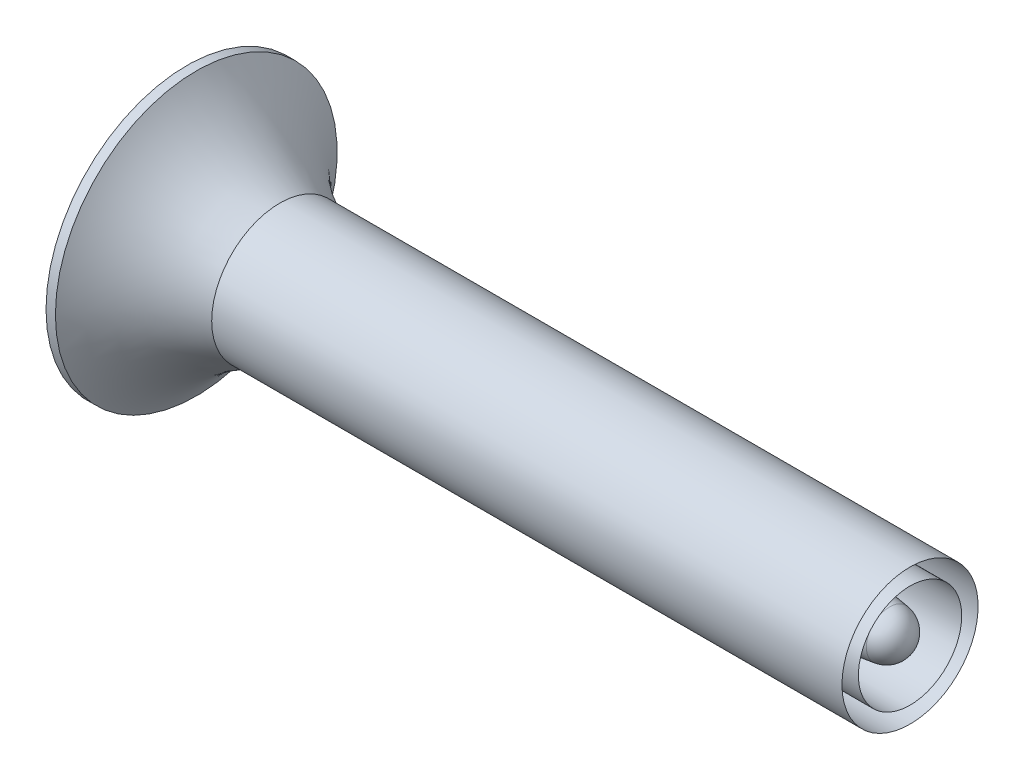
SolidWorks part; units mm, degrees
ref_plane "Front Plane" through (0, 0, 0) normal (0, 0, 1) x (1, 0, 0)
ref_plane "Top Plane" through (0, 0, 0) normal (0, 1, 0) x (1, 0, 0)
ref_plane "Right Plane" through (0, 0, 0) normal (1, 0, 0) x (0, 0, -1)
sketch "Sketch1" plane through (0, 0, 0) normal (0, 0, 1) x (1, 0, 0)
  line L0 (0, -3.81) -> (0, 0)
  line L1 (0, 3.81) -> (0.254, 3.81) construction
  line L2 (0.254, 3.81) -> (1.524, 2.54) construction
  line L3 (1.524, 2.54) -> (4.572, 1.397) construction
  line L4 (4.572, 1.397) -> (4.572, -1.397) construction
  line L5 (4.572, -1.397) -> (1.524, -2.54) construction
  line L6 (1.524, -2.54) -> (0.254, -3.81) construction
  line L7 (0.254, -3.81) -> (0, -3.81)
  line L8 (0.254, 3.81) -> (0.254, -3.81) construction
  line L9 (1.524, 2.54) -> (1.524, -2.54) construction
  line L10 (0, 0) -> (18.923, 0) construction
  line L11 (4.572, 1.397) -> (13.1767, 1.397) construction
  line L12 (4.572, -1.397) -> (13.1767, -1.397)
  line L13 (13.1767, -1.397) -> (19.0059, -0.6296)
  line L14 (19.0059, 0.6296) -> (13.1767, 1.397) construction
  line L15 (13.1767, 1.397) -> (13.1767, -1.397) construction
  line L16 (19.0059, -0.6296) -> (23.7879, 0) construction
  line L17 (23.7879, 0) -> (19.0059, 0.6296) construction
  line L18 (0, 0) -> (19.558, 0)
  line L19 (0, 0) -> (0, 3.81) construction
  arc A0 (19.558, 0) -> (19.0059, -0.6296) centre (18.923, 0) cw
  arc A1 (19.0059, 0.6296) -> (19.558, 0) centre (18.923, 0) cw construction
  arc A2 (4.572, -1.397) -> (0.254, -3.81) centre (4.572, -6.467) ccw
  point P14 (4.572, 0)
  point P26 (23.5984, -1.4211)
  point P27 (0, 0)
  point P28 (0, 0)
  point P29 (23.5984, -1.27)
  point P30 (24.1721, -1.27)
  point P31 (0, 0)
  point P32 (26.9794, -1.27)
  point P33 (0, 0)
  point P34 (0, 0)
  point P35 (0, 0)
  point P36 (0, 0)
  point P37 (0, 0)
  point P38 (0, 0)
  point P39 (0, 0)
  point P40 (0, 0)
  point P41 (0, 0)
  point P42 (0, 0)
  point P43 (0, 0)
  point P44 (0, 0)
  point P45 (0, 0)
  point P46 (0, 0)
  point P47 (0, 0)
  point P48 (0, 0)
  point P49 (0, 0)
  point P50 (0, 0)
  point P51 (0, 0)
  dimension "D10" = 0.635
  dimension "D1" = 7.62
  dimension "D2" = 4.318
  dimension "D3" = 45
  dimension "D4" = 45
  dimension "D5" = 5.08
  dimension "D6" = 2.794
  dimension "D7" = 4.572
  dimension "D8" = 19.558
  dimension "D9" = 15
revolve "Revolve1" add sketch "Sketch1" angle 360 about L18
sketch "Sketch2" plane through (0, 0, 0) normal (1, 0, 0) x (0, 0, -1)
  circle A1 centre (0, 0) radius 1.397
  circle A3 centre (0, 0) radius 1.397 construction
surface "Max Pre-Drill Diameter" sketch "Sketch2"
sketch "Sketch3" plane through (0, 0, 0) normal (-1, 0, 0) x (0, 0, 1)
  circle A0 centre (0, 0) radius 1.8415
  dimension "D1" = 3.683
surface "Thread Diameter" sketch "Sketch3"
